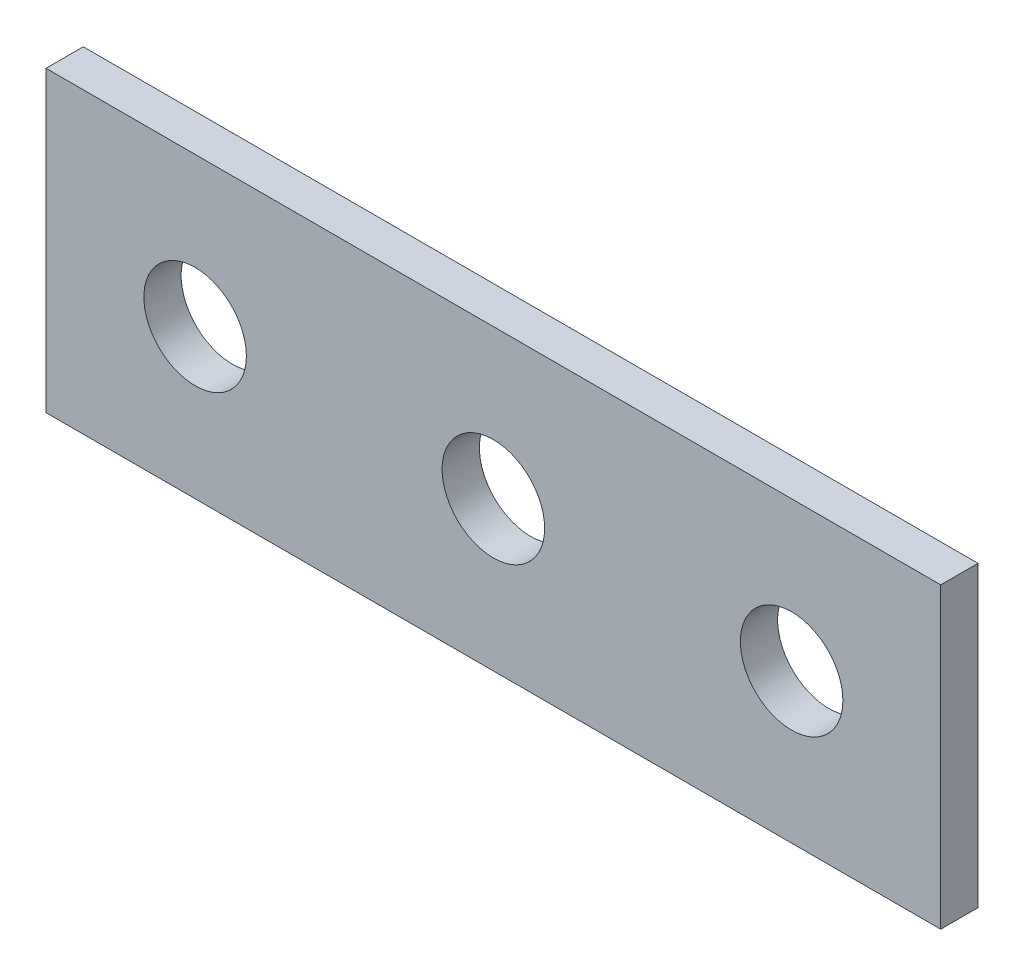
SolidWorks part; units mm, degrees
material "Low Carbon Steel"
ref_plane "Front Plane" through (0, 0, 0) normal (0, 0, 1) x (1, 0, 0)
ref_plane "Top Plane" through (0, 0, 0) normal (0, 1, 0) x (1, 0, 0)
ref_plane "Right Plane" through (0, 0, 0) normal (1, 0, 0) x (0, 0, -1)
sketch "Sketch1" plane through (0, 0, 0) normal (0, 0, 1) x (1, 0, 0)
  line L0 (-76.2, -25.4) -> (76.2, 25.4) construction
  line L1 (-76.2, 25.4) -> (76.2, 25.4)
  line L2 (-76.2, 25.4) -> (-76.2, -25.4)
  line L3 (-76.2, -25.4) -> (76.2, -25.4)
  line L4 (76.2, 25.4) -> (76.2, -25.4)
  dimension "D1" = 50.8
  dimension "D2" = 152.4
extrude "Boss-Extrude1" add sketch "Sketch1" along normal blind 6.35
hole_wizard "11/16 (0.6875) Diameter Hole1" positions "Sketch3" profile "Sketch4" hole size "11/16" standard "Peddi Ansi Inch" end condition through all
sketch "Sketch3" plane through (0, 0, 6.35) normal (0, 0, 1) x (1, 0, 0)
  line L0 (-50.8, 0) -> (50.8, 0) construction
  point P0 (0, 0)
  point P3 (50.8, 0)
  point P5 (-50.8, 0)
  dimension "D1" = 50.8
sketch "Sketch4" plane through (0, 0, 6.35) normal (1, 0, 0) x (0, -1, 0)
  line L0 (0, 0) -> (0, 6.35)
  line L1 (0, 6.35) -> (8.7312, 6.35)
  line L2 (8.7312, 6.35) -> (8.7312, 0)
  line L5 (8.7312, 0) -> (0, 0)
  line L11 (0, -6.35) -> (0, 107.95) construction
  dimension "Thru Hole Dia." = 17.4625
  dimension "Thru Hole Depth" = 6.35
other "Freeze***"
